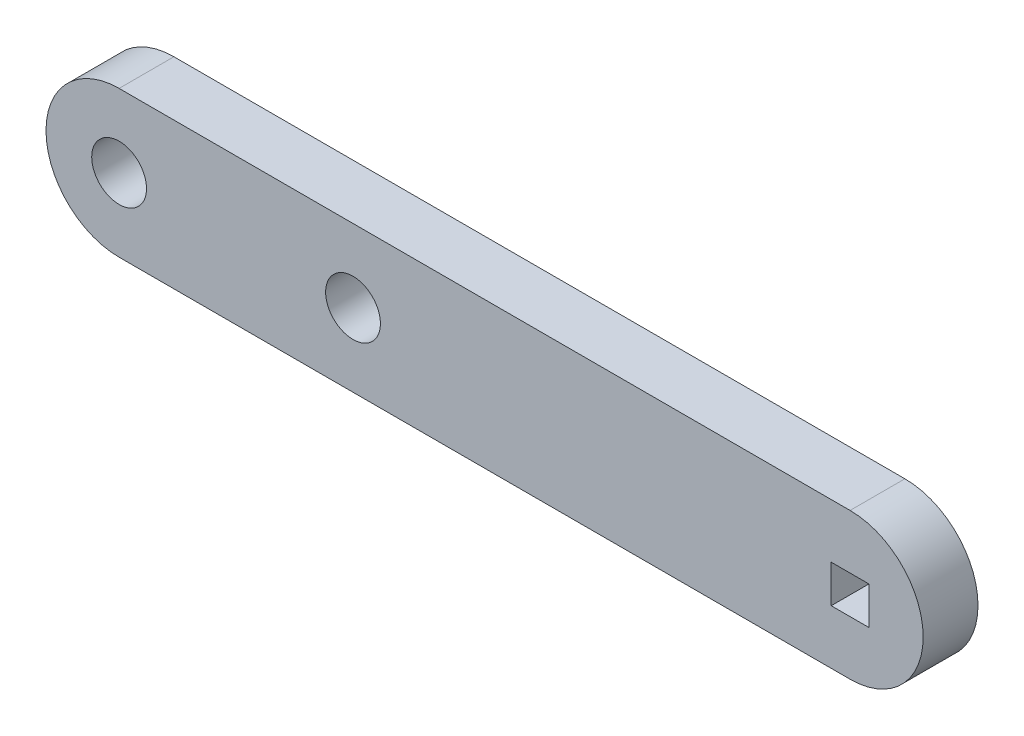
SolidWorks part; units mm, degrees
ref_plane "Front Plane" through (0, 0, 0) normal (0, 0, 1) x (1, 0, 0)
ref_plane "Top Plane" through (0, 0, 0) normal (0, 1, 0) x (1, 0, 0)
ref_plane "Right Plane" through (0, 0, 0) normal (1, 0, 0) x (0, 0, -1)
sketch "Sketch1" plane through (0, 0, 0) normal (0, 0, 1) x (1, 0, 0)
  line L0 (0, 0) -> (63.5, 0) construction
  line L1 (0, 6.35) -> (63.5, 6.35)
  line L2 (0, -6.35) -> (63.5, -6.35)
  line L4 (65.1383, -1.6383) -> (61.8617, -1.6383)
  line L5 (65.1383, -1.6383) -> (65.1383, 1.6383)
  line L6 (65.1383, 1.6383) -> (61.8617, 1.6383)
  line L7 (61.8617, -1.6383) -> (61.8617, 1.6383)
  line L8 (65.1383, -1.6383) -> (61.8617, 1.6383) construction
  line L9 (65.1383, 1.6383) -> (61.8617, -1.6383) construction
  arc A0 (0, 6.35) -> (0, -6.35) centre (0, 0) ccw
  arc A1 (63.5, -6.35) -> (63.5, 6.35) centre (63.5, 0) ccw
  circle A2 centre (0, 0) radius 2.3813
  circle A4 centre (20.32, 0) radius 2.3813
  point P3 (31.75, 0)
  point P10 (63.5, 0)
  dimension "D3" = 4.7625
  dimension "D4" = 3.2766
  dimension "D5" = 4.7625
  dimension "D1" = 63.5
  dimension "D2" = 12.7
  dimension "D6" = 20.32
extrude "Boss-Extrude1" add sketch "Sketch1" along normal blind 4.7625
